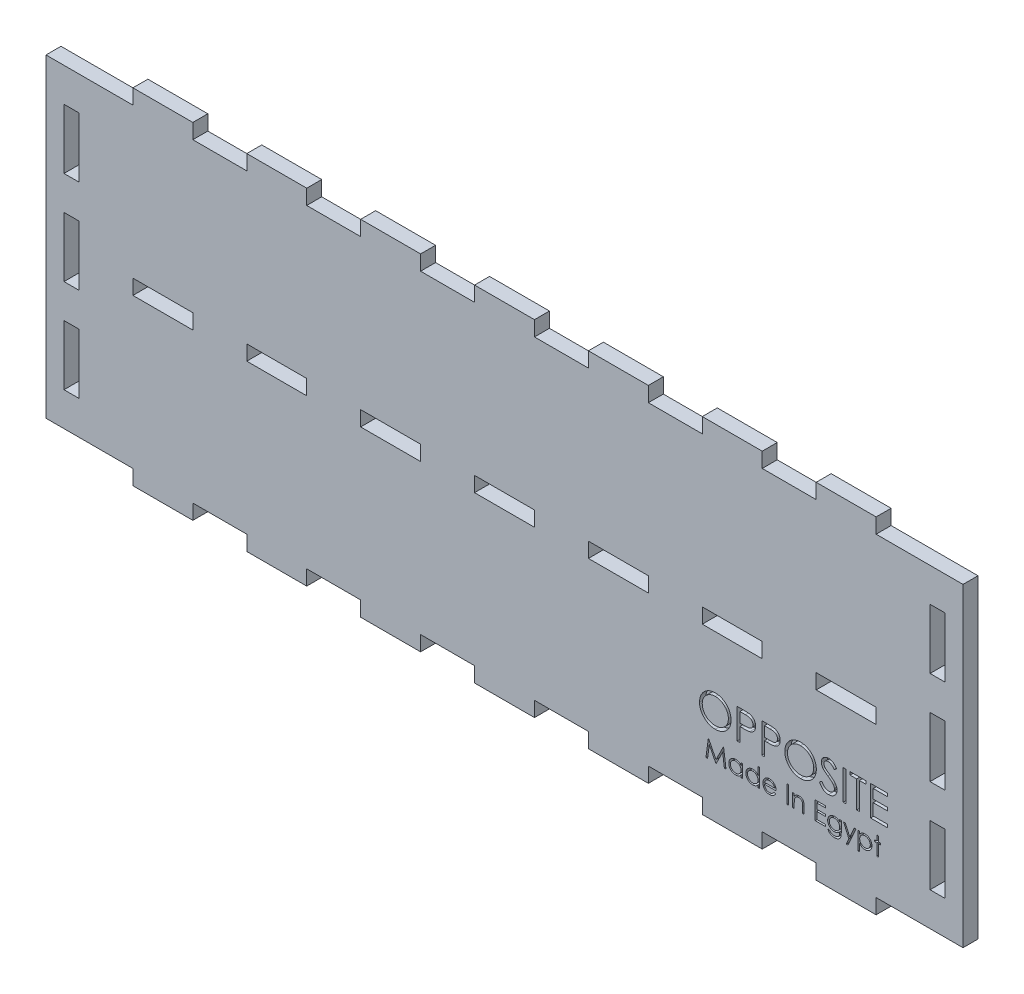
SolidWorks part; units mm, degrees
material "Beech"
ref_plane "Front" through (0, 0, 0) normal (0, 0, 1) x (1, 0, 0)
ref_plane "Top" through (0, 0, 0) normal (0, 1, 0) x (1, 0, 0)
ref_plane "Right" through (0, 0, 0) normal (1, 0, 0) x (0, 0, -1)
sketch "Sketch1" plane through (0, 0, 0) normal (0, 0, 1) x (1, 0, 0)
  line L0 (-76.5, 26.25) -> (-62, 26.25)
  line L1 (-76.5, -28.75) -> (76.5, -28.75) construction
  line L2 (-76.5, -28.75) -> (-76.5, 28.75) construction
  line L3 (-76.5, 28.75) -> (76.5, 28.75) construction
  line L4 (76.5, -28.75) -> (76.5, 28.75) construction
  line L5 (-76.5, -28.75) -> (76.5, 28.75) construction
  line L6 (-76.5, 28.75) -> (76.5, -28.75) construction
  line L7 (-73.5, -26.25) -> (73.5, -26.25) construction
  line L8 (-73.5, -26.25) -> (-73.5, 26.25) construction
  line L9 (-73.5, 26.25) -> (73.5, 26.25) construction
  line L10 (73.5, -26.25) -> (73.5, 26.25) construction
  line L11 (-73.5, -26.25) -> (73.5, 26.25) construction
  line L12 (-73.5, 26.25) -> (73.5, -26.25) construction
  line L13 (-62, 26.25) -> (-62, 28.75)
  line L14 (-62, 28.75) -> (-52, 28.75)
  line L15 (-52, 28.75) -> (-52, 26.25)
  line L16 (-52, 26.25) -> (-43, 26.25)
  line L17 (-43, 26.25) -> (-43, 28.75)
  line L18 (-43, 28.75) -> (-33, 28.75)
  line L19 (-33, 28.75) -> (-33, 26.25)
  line L20 (-33, 26.25) -> (-24, 26.25)
  line L21 (-24, 26.25) -> (-24, 28.75)
  line L22 (-24, 28.75) -> (-14, 28.75)
  line L23 (-14, 28.75) -> (-14, 26.25)
  line L24 (-14, 26.25) -> (-5, 26.25)
  line L25 (-5, 26.25) -> (-5, 28.75)
  line L26 (-5, 28.75) -> (5, 28.75)
  line L27 (0, 7.4006) -> (0, -7.3436) construction
  line L28 (10.0896, 0) -> (-10.0896, 0) construction
  line L29 (5, 26.25) -> (5, 28.75)
  line L30 (14, 26.25) -> (5, 26.25)
  line L31 (14, 28.75) -> (14, 26.25)
  line L32 (24, 28.75) -> (14, 28.75)
  line L33 (24, 26.25) -> (24, 28.75)
  line L34 (33, 26.25) -> (24, 26.25)
  line L35 (33, 28.75) -> (33, 26.25)
  line L36 (43, 28.75) -> (33, 28.75)
  line L37 (43, 26.25) -> (43, 28.75)
  line L38 (52, 26.25) -> (43, 26.25)
  line L39 (52, 28.75) -> (52, 26.25)
  line L40 (62, 28.75) -> (52, 28.75)
  line L41 (62, 26.25) -> (62, 28.75)
  line L42 (76.5, 26.25) -> (62, 26.25)
  line L43 (76.5, -26.25) -> (62, -26.25)
  line L44 (62, -26.25) -> (62, -28.75)
  line L45 (62, -28.75) -> (52, -28.75)
  line L46 (52, -28.75) -> (52, -26.25)
  line L47 (52, -26.25) -> (43, -26.25)
  line L48 (43, -26.25) -> (43, -28.75)
  line L49 (43, -28.75) -> (33, -28.75)
  line L50 (33, -28.75) -> (33, -26.25)
  line L51 (33, -26.25) -> (24, -26.25)
  line L52 (24, -26.25) -> (24, -28.75)
  line L53 (24, -28.75) -> (14, -28.75)
  line L54 (14, -28.75) -> (14, -26.25)
  line L55 (14, -26.25) -> (5, -26.25)
  line L56 (5, -26.25) -> (5, -28.75)
  line L57 (-5, -28.75) -> (5, -28.75)
  line L58 (-5, -26.25) -> (-5, -28.75)
  line L59 (-14, -26.25) -> (-5, -26.25)
  line L60 (-14, -28.75) -> (-14, -26.25)
  line L61 (-24, -28.75) -> (-14, -28.75)
  line L62 (-24, -26.25) -> (-24, -28.75)
  line L63 (-33, -26.25) -> (-24, -26.25)
  line L64 (-33, -28.75) -> (-33, -26.25)
  line L65 (-43, -28.75) -> (-33, -28.75)
  line L66 (-43, -26.25) -> (-43, -28.75)
  line L67 (-52, -26.25) -> (-43, -26.25)
  line L68 (-52, -28.75) -> (-52, -26.25)
  line L69 (-62, -28.75) -> (-52, -28.75)
  line L70 (-62, -26.25) -> (-62, -28.75)
  line L71 (-76.5, -26.25) -> (-62, -26.25)
  line L72 (76.5, 26.25) -> (76.5, -26.25)
  line L73 (-76.5, 26.25) -> (-76.5, -26.25)
  line L74 (-73.5, 10.625) -> (-71, 10.625)
  line L75 (73.5, 20.625) -> (71, 20.625)
  line L76 (73.5, 20.625) -> (73.5, 10.625)
  line L77 (73.5, 10.625) -> (71, 10.625)
  line L78 (71, 20.625) -> (71, 10.625)
  line L79 (73.5, 20.625) -> (71, 10.625) construction
  line L80 (73.5, 10.625) -> (71, 20.625) construction
  line L81 (-71, 20.625) -> (-71, 10.625)
  line L82 (-73.5, 20.625) -> (-71, 20.625)
  line L83 (-73.5, 20.625) -> (-73.5, 10.625)
  line L84 (73.5, 5) -> (73.5, -5)
  line L85 (73.5, 5) -> (71, 5)
  line L86 (71, 5) -> (71, -5)
  line L87 (73.5, -5) -> (71, -5)
  line L88 (-73.5, -5) -> (-71, -5)
  line L89 (-71, 5) -> (-71, -5)
  line L90 (-73.5, 5) -> (-71, 5)
  line L91 (-73.5, 5) -> (-73.5, -5)
  line L92 (73.5, -10.625) -> (73.5, -20.625)
  line L93 (73.5, -10.625) -> (71, -10.625)
  line L94 (71, -10.625) -> (71, -20.625)
  line L95 (73.5, -20.625) -> (71, -20.625)
  line L96 (-73.5, -20.625) -> (-71, -20.625)
  line L97 (-71, -10.625) -> (-71, -20.625)
  line L98 (-73.5, -10.625) -> (-71, -10.625)
  line L99 (-73.5, -10.625) -> (-73.5, -20.625)
  line L100 (-43, -1.25) -> (-43, 1.25)
  line L101 (-62, -1.25) -> (-52, -1.25)
  line L102 (-62, -1.25) -> (-62, 1.25)
  line L103 (-62, 1.25) -> (-52, 1.25)
  line L104 (-52, -1.25) -> (-52, 1.25)
  line L105 (-62, -1.25) -> (-52, 1.25) construction
  line L106 (-62, 1.25) -> (-52, -1.25) construction
  line L107 (-43, -1.25) -> (-33, -1.25)
  line L108 (-33, -1.25) -> (-33, 1.25)
  line L109 (-43, 1.25) -> (-33, 1.25)
  line L110 (-24, -1.25) -> (-24, 1.25)
  line L111 (-24, -1.25) -> (-14, -1.25)
  line L112 (-14, -1.25) -> (-14, 1.25)
  line L113 (-24, 1.25) -> (-14, 1.25)
  line L114 (-5, -1.25) -> (-5, 1.25)
  line L115 (-5, -1.25) -> (5, -1.25)
  line L116 (5, -1.25) -> (5, 1.25)
  line L117 (-5, 1.25) -> (5, 1.25)
  line L118 (14, -1.25) -> (14, 1.25)
  line L119 (14, -1.25) -> (24, -1.25)
  line L120 (24, -1.25) -> (24, 1.25)
  line L121 (14, 1.25) -> (24, 1.25)
  line L122 (33, -1.25) -> (33, 1.25)
  line L123 (33, -1.25) -> (43, -1.25)
  line L124 (43, -1.25) -> (43, 1.25)
  line L125 (33, 1.25) -> (43, 1.25)
  line L126 (52, -1.25) -> (52, 1.25)
  line L127 (52, -1.25) -> (62, -1.25)
  line L128 (62, -1.25) -> (62, 1.25)
  line L129 (52, 1.25) -> (62, 1.25)
  point P0 (0, 0)
  point P6 (0, 0)
  point P31 (0, 28.75)
  point P80 (72.25, 15.625)
  point P81 (72.25, 20.625)
  point P86 (-72.25, 10.625)
  point P87 (-57, 0)
  dimension "D1" = 57.5
  dimension "D2" = 153
  dimension "D3" = 2.5
  dimension "D4" = 3
  dimension "D5" = 10
  dimension "D6" = 9
  dimension "D7" = 11.5
  dimension "D8" = 14.5
  dimension "D9" = 14.5
  dimension "D10" = 14.5
  dimension "D11" = 14.5
  dimension "D12" = 5.625
  dimension "D14" = 5.625
  dimension "D15" = 9
  dimension "D17" = 9
  dimension "D13" = 3
  dimension "D16" = 7
extrude "Boss-Extrude1" add sketch "Sketch1" along normal blind 2.5
sketch "Sketch2" plane through (0, 0, 2.5) normal (0, 0, 1) x (1, 0, 0)
  line L0 (29.1314, -15.2213) -> (67.1645, -15.2213) construction
  line L1 (29.1314, -20.2213) -> (67.1645, -20.2213) construction
  text T0 "OPPOSITE" font "Century Gothic" height 5
  text T1 "Made In Egypt" font "Century Gothic" height 3
  dimension "D1" = 5
extrude "Cut-Extrude1" cut sketch "Sketch2" against normal blind 1
